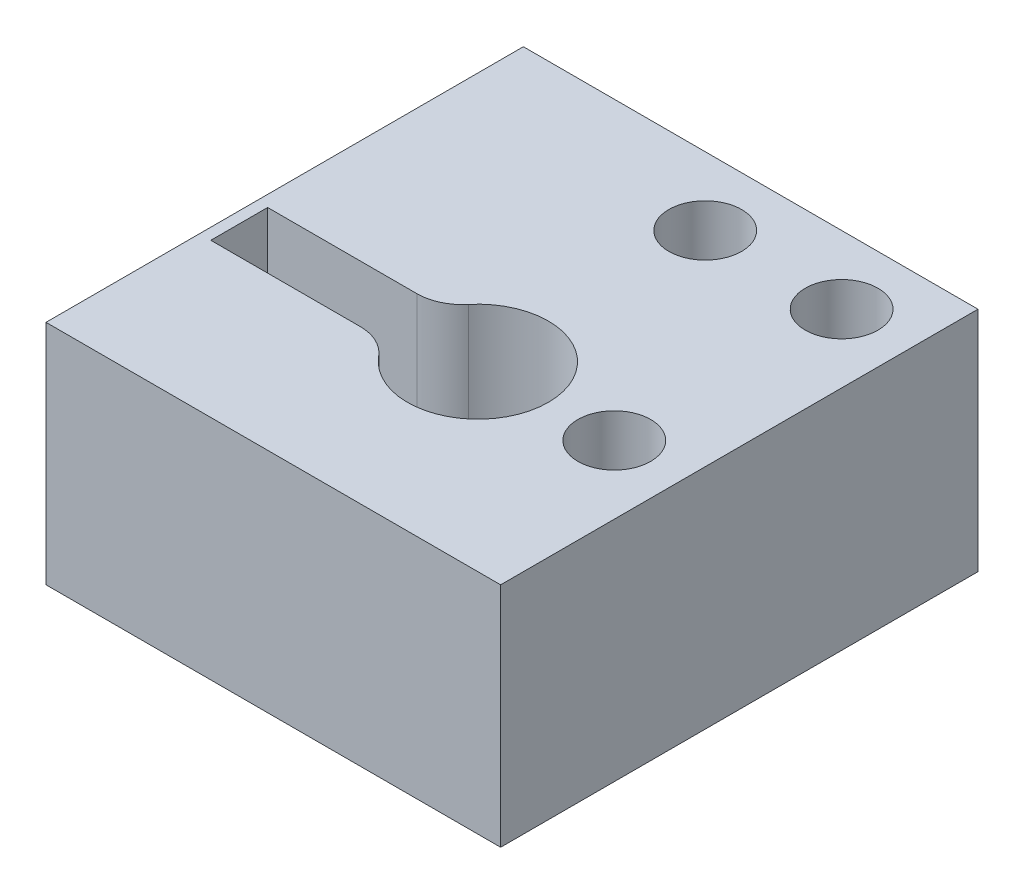
SolidWorks part; units mm, degrees
ref_plane "前视基准面" through (0, 0, 0) normal (0, 0, 1) x (1, 0, 0)
ref_plane "上视基准面" through (0, 0, 0) normal (0, 1, 0) x (1, 0, 0)
ref_plane "右视基准面" through (0, 0, 0) normal (1, 0, 0) x (0, 0, -1)
other "Configuration Table"
sketch "草图1" plane through (0, 0, 0) normal (0, 1, 0) x (1, 0, 0)
  line L1 (-10, -10.5) -> (10, -10.5)
  line L2 (-10, -10.5) -> (-10, 10.5)
  line L3 (-10, 10.5) -> (10, 10.5)
  line L4 (10, -10.5) -> (10, 10.5)
  line L5 (0, 10.5) -> (0, -10.5) construction
  line L6 (-10, 0) -> (10, 0) construction
  point P0 (0, 0)
  dimension "D1" = 20
  dimension "D2" = 21
extrude "凸台-拉伸1" add sketch "草图1" along normal blind 10
sketch "草图2" plane through (0, 10, 0) normal (0, 1, 0) x (1, 0, 0)
  line L6 (-10, 10.5) -> (-10, -10.5) construction
  line L7 (-1.8368, -1.25) -> (-10, -1.25)
  line L8 (-1.8368, -1.25) -> (-1.8368, -3.75) construction
  line L9 (-1.8368, -3.75) -> (-10, -3.75)
  line L10 (-10, -1.25) -> (-10, -3.75)
  line L12 (-10, -10.5) -> (10, -10.5) construction
  line L13 (10, -10.5) -> (10, 10.5) construction
  arc A1 (-1.8368, -3.75) -> (-1.8368, -1.25) centre (1, -2.5) ccw
  point P8 (0, 0)
  dimension "D1" = 6.2
  dimension "D2" = 2.5
  dimension "D3" = 9
  dimension "D4" = 8
extrude "切除-拉伸1" cut sketch "草图2" against normal through all
fillet "圆角2" radius 2 2 edges at (-1.8368, 5, 3.75) (-1.8368, 5, 1.25)
sketch "草图3" plane through (0, 10, 0) normal (0, 1, 0) x (1, 0, 0)
  line L0 (1, -2.5) -> (1, 10.5) construction
  line L1 (10, 10.5) -> (-10, 10.5) construction
  line L2 (7, -10.5) -> (7, 10.5) construction
  line L3 (-10, -10.5) -> (10, -10.5) construction
  circle A1 centre (1, 7.5) radius 1.6
  circle A2 centre (7, 7.5) radius 1.6
  circle A3 centre (7, -2.5) radius 1.6
  point P14 (0, 0)
  dimension "D1" = 3.2
  dimension "D4" = 3.2
  dimension "D5" = 3.2
  dimension "D2" = 10
  dimension "D3" = 6
extrude "切除-拉伸2" cut sketch "草图3" against normal through all
sketch "草图4" plane through (0, 10, 0) normal (0, 1, 0) x (1, 0, 0)
  line L0 (-10, 10.5) -> (-10, -1.25) construction
  line L1 (-10, -1.25) -> (-9.5, -1.25)
  line L2 (-10, -1.25) -> (-10, -3.75)
  line L3 (-10, -3.75) -> (-9.5, -3.75)
  line L4 (-9.5, -1.25) -> (-9.5, -3.75)
  line L5 (-2.9303, -1.25) -> (-10, -1.25) construction
  line L6 (-10, -3.75) -> (-2.9303, -3.75) construction
  dimension "D1" = 0.5
extrude "凸台-拉伸2" add sketch "草图4" against normal blind 10
